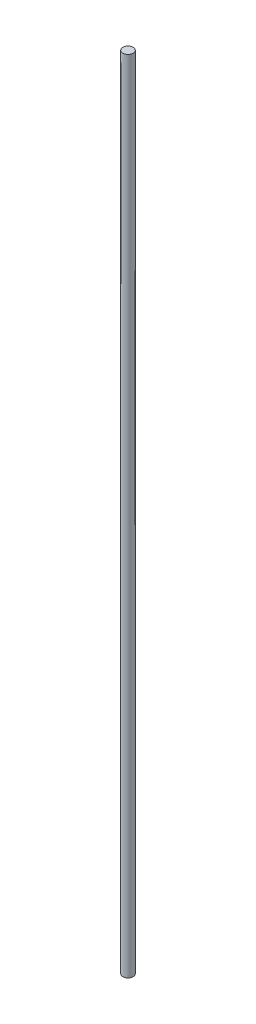
SolidWorks part; units mm, degrees
material "黄铜"
ref_plane "前视基准面" through (0, 0, 0) normal (0, 0, 1) x (1, 0, 0)
ref_plane "上视基准面" through (0, 0, 0) normal (0, 1, 0) x (1, 0, 0)
ref_plane "右视基准面" through (0, 0, 0) normal (1, 0, 0) x (0, 0, -1)
sketch "草图1" plane through (0, 0, 0) normal (0, 1, 0) x (1, 0, 0)
  circle A0 centre (0, 0) radius 1.2
  dimension "D1" = 2.4
extrude "凸台-拉伸1" add sketch "草图1" along normal blind 186
sketch "草图2" plane through (0, 0, 0) normal (0, -1, 0) x (1, 0, 0)
  point P0 (0, 0)
sketch "草图3" plane through (0, 186, 0) normal (0, 1, 0) x (1, 0, 0)
  point P0 (0, 0)
